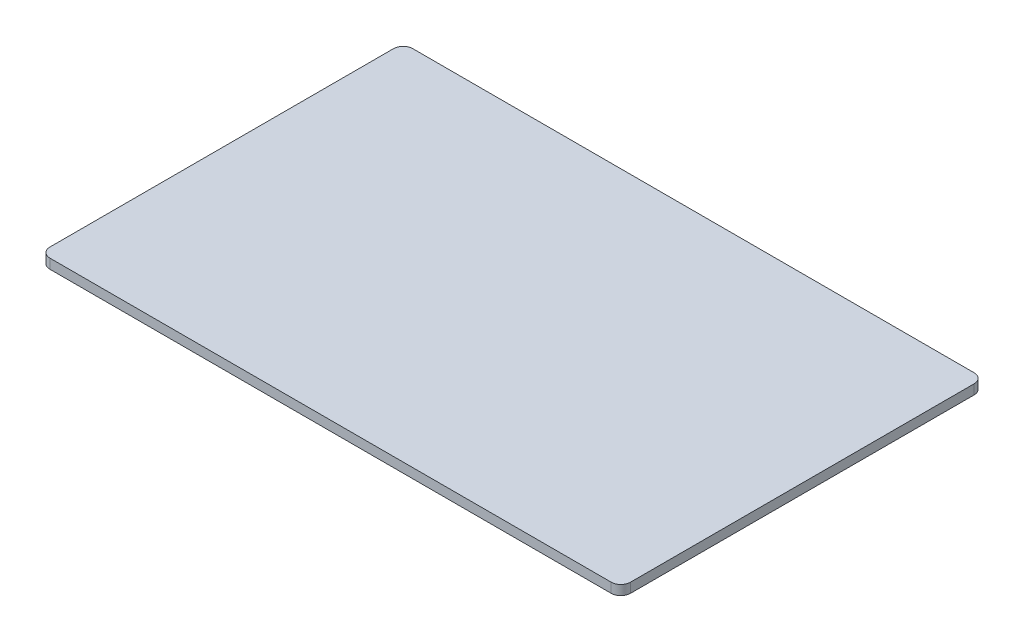
SolidWorks part; units mm, degrees
ref_plane "前视基准面" through (0, 0, 0) normal (0, 0, 1) x (1, 0, 0)
ref_plane "上视基准面" through (0, 0, 0) normal (0, 1, 0) x (1, 0, 0)
ref_plane "右视基准面" through (0, 0, 0) normal (1, 0, 0) x (0, 0, -1)
other "Configuration Table"
sketch "草图1" plane through (0, 0, 0) normal (0, 1, 0) x (1, 0, 0)
  line L1 (-59.005, 36.2189) -> (60.995, 36.2189)
  line L2 (-59.005, 36.2189) -> (-59.005, -38.7811)
  line L3 (-59.005, -38.7811) -> (60.995, -38.7811)
  line L4 (60.995, 36.2189) -> (60.995, -38.7811)
  dimension "D1" = 120
  dimension "D2" = 75
extrude "凸台-拉伸1" add sketch "草图1" along normal blind 2
fillet "圆角1" radius 2 4 edges at (-59.005, 1, -36.2189) (60.995, 1, -36.2189) (60.995, 1, 38.7811) (-59.005, 1, 38.7811)
